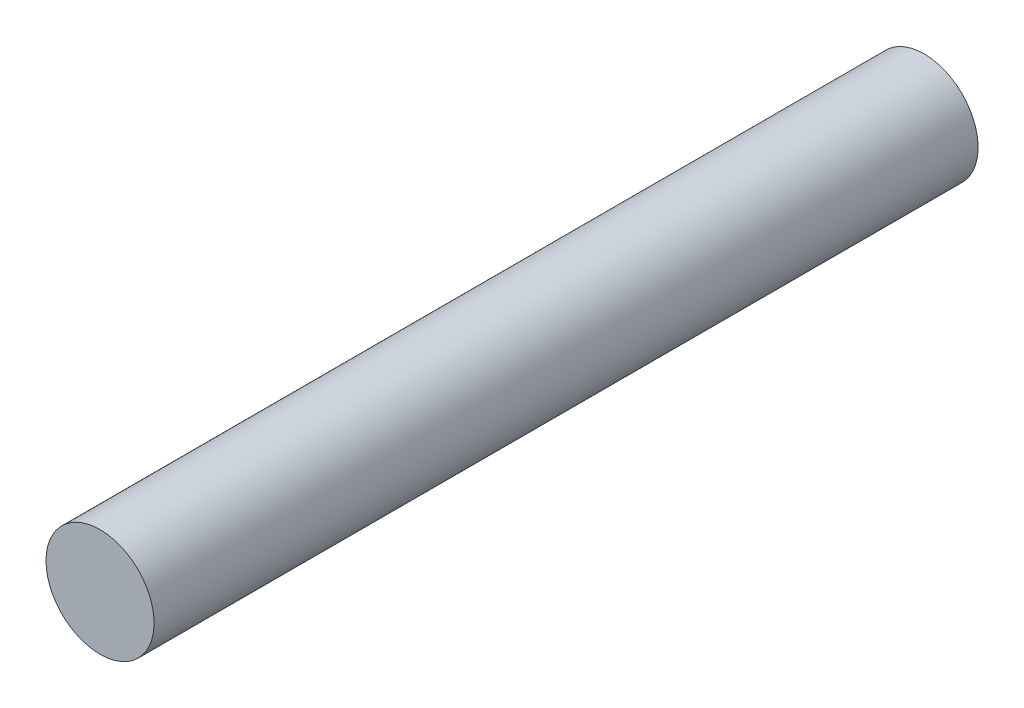
SolidWorks part; units mm, degrees
material "AISI 304"
ref_plane "Front Plane" through (0, 0, 0) normal (0, 0, 1) x (1, 0, 0)
ref_plane "Top Plane" through (0, 0, 0) normal (0, 1, 0) x (1, 0, 0)
ref_plane "Right Plane" through (0, 0, 0) normal (1, 0, 0) x (0, 0, -1)
sketch "Sketch1" plane through (0, 0, 0) normal (0, 0, 1) x (1, 0, 0)
  circle A0 centre (0, 0) radius 4
  dimension "D1" = 8
extrude "Boss-Extrude1" add sketch "Sketch1" along normal blind 61
